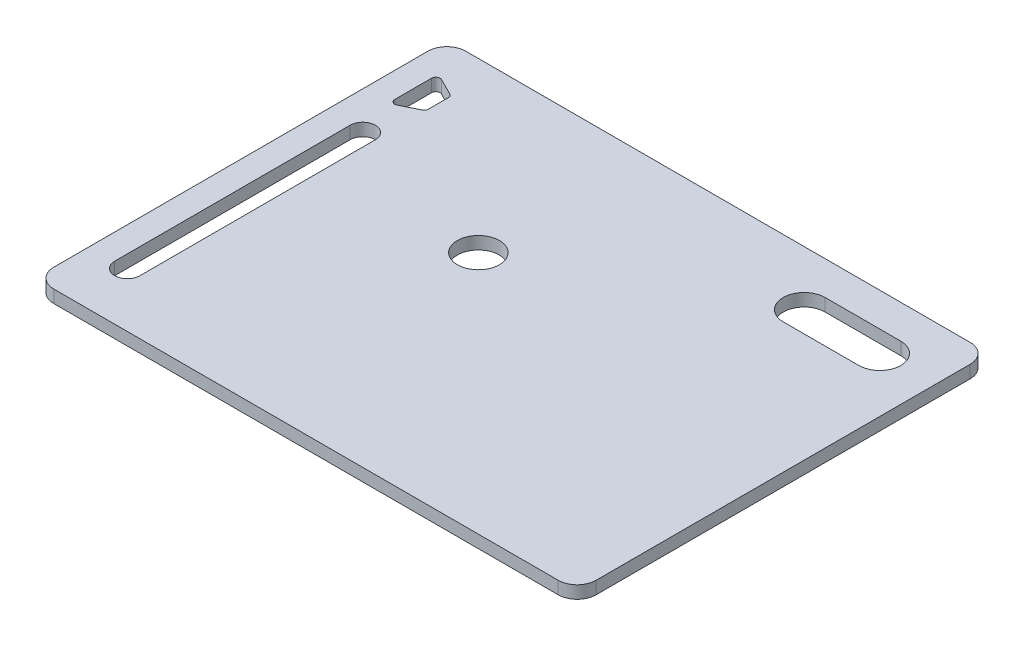
SolidWorks part; units mm, degrees
ref_plane "Front Plane" through (0, 0, 0) normal (0, 0, 1) x (1, 0, 0)
ref_plane "Top Plane" through (0, 0, 0) normal (0, 1, 0) x (1, 0, 0)
ref_plane "Right Plane" through (0, 0, 0) normal (1, 0, 0) x (0, 0, -1)
sketch "Sketch1" plane through (0, 0, 0) normal (0, 1, 0) x (1, 0, 0)
  line L1 (-409.575, -311.15) -> (409.575, -311.15)
  line L2 (-409.575, -311.15) -> (-409.575, 311.15)
  line L3 (-409.575, 311.15) -> (409.575, 311.15)
  line L4 (409.575, -311.15) -> (409.575, 311.15)
  line L5 (-409.575, -311.15) -> (409.575, 311.15) construction
  line L6 (-409.575, 311.15) -> (409.575, -311.15) construction
  point P0 (0, 0)
  dimension "D1" = 622.3
  dimension "D2" = 819.15
extrude "Boss-Extrude1" add sketch "Sketch1" along normal blind 19.05
fillet "Fillet1" radius 28.575 4 edges at (-409.575, 9.525, -311.15) (409.575, 9.525, -311.15) (-409.575, 9.525, 311.15) (409.575, 9.525, 311.15)
sketch "Sketch2" plane through (0, 19.05, 0) normal (0, 1, 0) x (1, 0, 0)
  line L0 (-409.575, 282.575) -> (-409.575, -282.575) construction
  line L1 (381, 311.15) -> (-381, 311.15) construction
  circle A0 centre (-107.95, 57.15) radius 31.75
  dimension "D1" = 63.5
  dimension "D2" = 301.625
  dimension "D3" = 254
extrude "Cut-Extrude1" cut sketch "Sketch2" against normal through all
sketch "Sketch3" plane through (0, 19.05, 0) normal (0, 1, 0) x (1, 0, 0)
  line L0 (-352.425, 127) -> (-352.425, -228.6) construction
  line L1 (-333.375, 127) -> (-333.375, -228.6)
  line L2 (-371.475, 127) -> (-371.475, -228.6)
  line L3 (-409.575, 282.575) -> (-409.575, -282.575) construction
  line L4 (-352.425, -247.65) -> (-352.425, -311.15) construction
  line L5 (-381, -311.15) -> (381, -311.15) construction
  arc A0 (-333.375, 127) -> (-371.475, 127) centre (-352.425, 127) ccw
  arc A1 (-371.475, -228.6) -> (-333.375, -228.6) centre (-352.425, -228.6) ccw
  point P2 (-352.425, -50.8)
  point P13 (-352.425, 146.05)
  dimension "D1" = 38.1
  dimension "D2" = 38.1
  dimension "D3" = 63.5
  dimension "D4" = 393.7
extrude "Cut-Extrude2" cut sketch "Sketch3" against normal through all
sketch "Sketch4" plane through (0, 19.05, 0) normal (0, 1, 0) x (1, 0, 0)
  line L0 (-371.475, 260.35) -> (-371.475, 184.15)
  line L1 (-371.475, 184.15) -> (-333.375, 203.2)
  line L2 (-333.375, 203.2) -> (-333.375, 241.3)
  line L3 (-333.375, 241.3) -> (-371.475, 260.35)
  line L4 (-371.475, 222.25) -> (-333.375, 222.25) construction
  line L5 (381, 311.15) -> (-381, 311.15) construction
  line L6 (-371.475, 127) -> (-371.475, -228.6) construction
  line L7 (-333.375, -228.6) -> (-333.375, 127) construction
  dimension "D1" = 76.2
  dimension "D2" = 38.1
  dimension "D3" = 50.8
extrude "Cut-Extrude3" cut sketch "Sketch4" against normal through all
fillet "Fillet2" radius 6.35 4 edges at (-333.375, 9.525, -241.3) (-333.375, 9.525, -203.2) (-371.475, 9.525, -184.15) (-371.475, 9.525, -260.35)
sketch "Sketch5" plane through (0, 19.05, 0) normal (0, 1, 0) x (1, 0, 0)
  line L0 (327.025, 228.6) -> (212.725, 228.6) construction
  line L1 (327.025, 196.85) -> (212.725, 196.85)
  line L2 (327.025, 260.35) -> (212.725, 260.35)
  line L3 (381, 311.15) -> (-381, 311.15) construction
  line L4 (409.575, -282.575) -> (409.575, 282.575) construction
  arc A0 (327.025, 196.85) -> (327.025, 260.35) centre (327.025, 228.6) ccw
  arc A1 (212.725, 260.35) -> (212.725, 196.85) centre (212.725, 228.6) ccw
  point P2 (269.875, 228.6)
  point P9 (358.775, 228.6)
  dimension "D1" = 63.5
  dimension "D2" = 114.3
  dimension "D3" = 50.8
  dimension "D4" = 50.8
extrude "Cut-Extrude4" cut sketch "Sketch5" against normal through all
